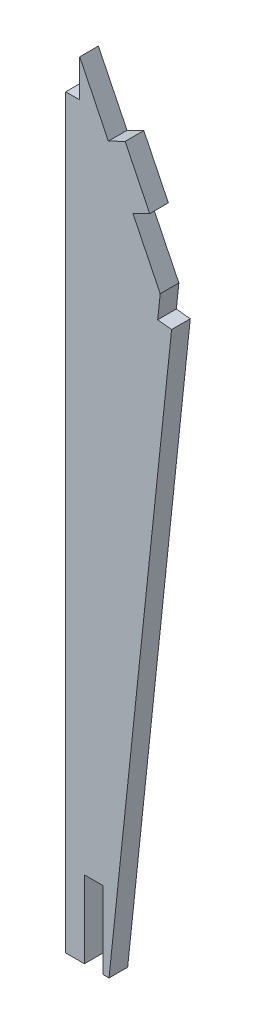
SolidWorks part; units mm, degrees
ref_plane "前视基准面" through (0, 0, 0) normal (0, 0, 1) x (1, 0, 0)
ref_plane "上视基准面" through (0, 0, 0) normal (0, 1, 0) x (1, 0, 0)
ref_plane "右视基准面" through (0, 0, 0) normal (1, 0, 0) x (0, 0, -1)
sketch "草图1" plane through (0, 0, 0) normal (0, 0, 1) x (1, 0, 0)
  line L0 (8.3908, 89.3159) -> (8.3908, 85.3159)
  line L1 (8.3908, 85.3159) -> (6.8908, 85.3159)
  line L2 (6.8908, 85.3159) -> (6.8908, 5.4079)
  line L3 (8.3908, 89.3159) -> (11.4594, 83.0243)
  line L4 (11.4594, 83.0243) -> (13.2569, 83.9011)
  line L5 (13.2569, 83.9011) -> (15.8872, 78.5083)
  line L6 (15.8872, 78.5083) -> (14.0896, 77.6316)
  line L7 (14.0896, 77.6316) -> (17.0127, 71.6382)
  line L8 (6.8908, 5.4079) -> (8.8908, 5.4079)
  line L9 (8.8908, 5.4079) -> (8.8908, 13.6579)
  line L10 (8.8908, 13.6579) -> (10.8908, 13.6579)
  line L11 (18.2355, 68.9332) -> (11.528, 5.4079)
  line L12 (10.8908, 13.6579) -> (10.8908, 5.4079)
  line L13 (10.8908, 5.4079) -> (11.528, 5.4079)
  line L14 (17.0127, 71.6382) -> (16.7437, 69.0907)
  line L15 (16.7437, 69.0907) -> (18.2355, 68.9332)
  line L16 (17.0127, 71.6382) -> (16.7437, 69.0907)
  line L17 (16.7437, 69.0907) -> (18.2355, 68.9332)
extrude "凸台-拉伸1" add sketch "草图1" along normal blind 2 contours L15 L14 L7 L6 L5 L4 L3 L0 L1 L2 L8 L9 L10 L12 L13 L11
